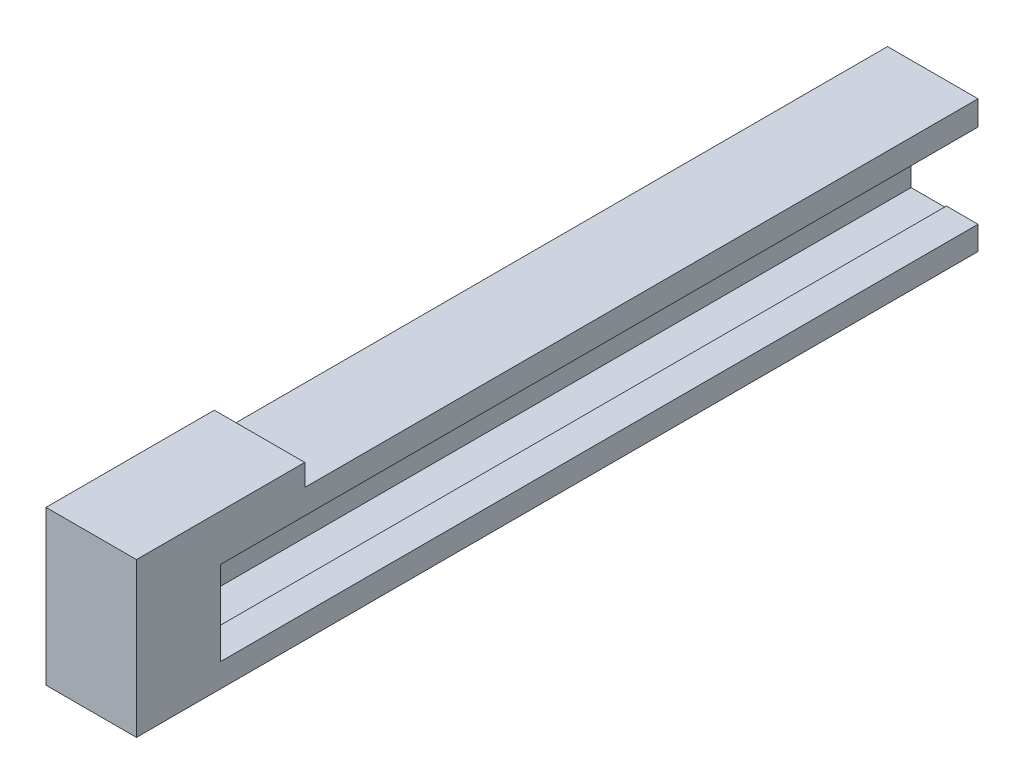
SolidWorks part; units mm, degrees
ref_plane "Front Plane" through (0, 0, 0) normal (0, 0, 1) x (1, 0, 0)
ref_plane "Top Plane" through (0, 0, 0) normal (0, 1, 0) x (1, 0, 0)
ref_plane "Right Plane" through (0, 0, 0) normal (1, 0, 0) x (0, 0, -1)
sketch "Sketch2" plane through (0, 0, 0) normal (0, 0, 1) x (1, 0, 0)
  line L0 (16.75, 6) -> (13, 6) construction
  line L1 (9, 6) -> (13, 6) construction
  line L2 (9, 8.5) -> (9, 6) construction
  line L3 (5, 8.5) -> (9, 8.5) construction
  line L4 (5, 13.5) -> (9, 13.5) construction
  line L5 (9, 16) -> (9, 13.5) construction
  line L6 (9, 16) -> (13, 16) construction
  line L7 (16.75, 16) -> (13, 16) construction
  line L8 (16.75, 6) -> (13, 6)
  line L9 (9, 6) -> (13, 6)
  line L10 (9, 8.5) -> (9, 6)
  line L11 (5, 8.5) -> (9, 8.5)
  line L12 (5, 13.5) -> (9, 13.5)
  line L13 (9, 16) -> (9, 13.5)
  line L14 (9, 16) -> (13, 16)
  line L15 (16.75, 16) -> (13, 16)
  line L16 (16.75, 26) -> (13, 26)
  line L17 (-1, 26) -> (13, 26)
  line L18 (-1, 26) -> (-1, 21.5)
  line L19 (-1, 21.5) -> (-1, 21.5)
  line L20 (5, 13.8) -> (8.7, 13.8)
  line L21 (8.7, 16.3) -> (8.7, 13.8)
  line L22 (8.7, 16.3) -> (13, 16.3)
  line L23 (16.75, 16.3) -> (13, 16.3)
  line L24 (5, 8.3) -> (8.8, 8.3)
  line L25 (8.8, 8.3) -> (8.8, 5.8)
  line L26 (8.8, 5.8) -> (13, 5.8)
  line L27 (16.75, 5.8) -> (13, 5.8)
  line L28 (13, 16.3) -> (13, 16)
  line L29 (13, 5.8) -> (13, 6)
  line L30 (16.75, 5.8) -> (16.75, 6)
  line L31 (16.75, 16.3) -> (16.75, 16)
  line L32 (6, 13.5) -> (6, 13.8)
  line L33 (6, 8.5) -> (6, 8.3)
  line L34 (5, 20) -> (5, 13.5) construction
  line L36 (16.75, 16.3) -> (8.7, 16.3)
  line L37 (16.75, 16.3) -> (16.75, 18.9132)
  line L38 (16.75, 18.9132) -> (8.7, 18.9132)
  line L39 (8.7, 16.3) -> (8.7, 18.9132)
  line L40 (8.7, 18.9132) -> (6, 18.9132)
  line L41 (8.7, 18.9132) -> (8.7, 13.8)
  line L42 (8.7, 13.8) -> (6, 13.8)
  line L43 (6, 18.9132) -> (6, 13.8)
  line L44 (16.75, 5.8) -> (8.8, 5.8)
  line L45 (16.75, 5.8) -> (16.75, 3.1868)
  line L46 (16.75, 3.1868) -> (8.8, 3.1868)
  line L47 (8.8, 5.8) -> (8.8, 3.1868)
  line L48 (8.8, 3.1868) -> (6, 3.1868)
  line L49 (8.8, 3.1868) -> (8.8, 8.3)
  line L50 (8.8, 8.3) -> (6, 8.3)
  line L51 (6, 3.1868) -> (6, 8.3)
  dimension "D4" = 1
  dimension "D1" = 10
  dimension "D2" = 0.3
  dimension "D3" = 0.2
extrude "Boss-Extrude3" add sketch "Sketch2" along normal blind 90 contours L31 L23 L28 L15 | L39 L22 L23 L37 L38 | L40 L43 L20 L21 L39 | L51 L48 L47 L25 L24 | L26 L47 L46 L45 L27 | L27 L30 L8 L29
sketch "Sketch3" plane through (0, 0, 90) normal (0, 0, 1) x (1, 0, 0)
  line L0 (6, 8.3) -> (6, 3.1868) construction
  line L1 (6, 3.1868) -> (16.75, 3.1868) construction
  line L2 (16.75, 3.1868) -> (16.75, 6) construction
  line L3 (16.75, 6) -> (13, 6) construction
  line L4 (13, 6) -> (13, 5.8) construction
  line L5 (13, 5.8) -> (8.8, 5.8) construction
  line L6 (8.8, 5.8) -> (8.8, 8.3) construction
  line L7 (8.8, 8.3) -> (6, 8.3) construction
  line L8 (16.75, 16) -> (16.75, 18.9132)
  line L9 (16.75, 18.9132) -> (6, 18.9132)
  line L10 (6, 18.9132) -> (6, 13.8)
  line L11 (6, 13.8) -> (8.7, 13.8)
  line L12 (8.7, 13.8) -> (8.7, 16.3)
  line L13 (8.7, 16.3) -> (13, 16.3)
  line L14 (13, 16.3) -> (13, 16)
  line L15 (13, 16) -> (16.75, 16)
  line L16 (16.75, 16) -> (16.75, 18.9132)
  line L17 (16.75, 18.9132) -> (6, 18.9132)
  line L18 (6, 18.9132) -> (6, 13.8)
  line L19 (6, 13.8) -> (8.7, 13.8)
  line L20 (8.7, 13.8) -> (8.7, 16.3)
  line L21 (8.7, 16.3) -> (13, 16.3)
  line L22 (13, 16.3) -> (13, 16)
  line L23 (13, 16) -> (16.75, 16)
  line L24 (18.5681, 6) -> (18.5681, 16) construction
  line L25 (18.5681, 16) -> (13, 16) construction
  line L26 (13, 16) -> (13, 6) construction
  line L27 (13, 6) -> (18.5681, 6) construction
  line L28 (18.5681, 6) -> (18.5681, 16)
  line L29 (18.5681, 16) -> (13, 16)
  line L30 (13, 16) -> (13, 6)
  line L31 (13, 6) -> (18.5681, 6)
  line L32 (6, 8.3) -> (6, 3.1868)
  line L33 (6, 3.1868) -> (16.75, 3.1868)
  line L34 (16.75, 3.1868) -> (16.75, 6)
  line L35 (16.75, 6) -> (13, 6)
  line L36 (13, 6) -> (13, 5.8)
  line L37 (13, 5.8) -> (8.8, 5.8)
  line L38 (8.8, 5.8) -> (8.8, 8.3)
  line L39 (8.8, 8.3) -> (6, 8.3)
  line L40 (6, 13.8) -> (6, 8.3)
  line L41 (16.75, 16) -> (16.75, 6)
  line M42 (16.75, 16) -> (16.75, 18.9132)
  line M43 (16.75, 18.9132) -> (6, 18.9132)
  line M44 (6, 18.9132) -> (6, 13.8)
  line M45 (6, 13.8) -> (8.7, 13.8)
  line M46 (8.7, 13.8) -> (8.7, 16.3)
  line M47 (8.7, 16.3) -> (13, 16.3)
  line M48 (13, 16.3) -> (13, 16)
  line M49 (13, 16) -> (16.75, 16)
  dimension "D1" = 0
extrude "Boss-Extrude4" add sketch "Sketch3" along normal blind 10 contours L40 L39 L38 L37 L36 L30 M45 M48 M47 M46 | L30 L31 L28 L29 M49 | M49 M42 M43 M44 M45 M46 M47 M48 | L38 L39 L32 L33 L34 L31 L36 L37
sketch "Sketch4" plane through (0, 0, 100) normal (0, 0, 1) x (1, 0, 0)
  line L0 (16.75, 3.1868) -> (16.75, 18.9132) construction
  line L1 (6, 18.9132) -> (16.75, 18.9132)
  line L2 (6, 18.9132) -> (6, 21.4917)
  line L3 (6, 21.4917) -> (16.75, 21.4917)
  line L4 (16.75, 18.9132) -> (16.75, 21.4917)
extrude "Boss-Extrude5" add sketch "Sketch4" against normal blind 20
sketch "Sketch5" plane through (0, 0, 100) normal (0, 0, 1) x (1, 0, 0)
  line L1 (16.75, 21.4917) -> (-3.25, 21.4917)
  line L2 (16.75, 21.4917) -> (16.75, 26.4917)
  line L3 (16.75, 26.4917) -> (-3.25, 26.4917)
  line L4 (-3.25, 21.4917) -> (-3.25, 26.4917)
  dimension "D1" = 20
  dimension "D2" = 5
extrude "Boss-Extrude6" [suppressed] add sketch "Sketch5" against normal blind 2
